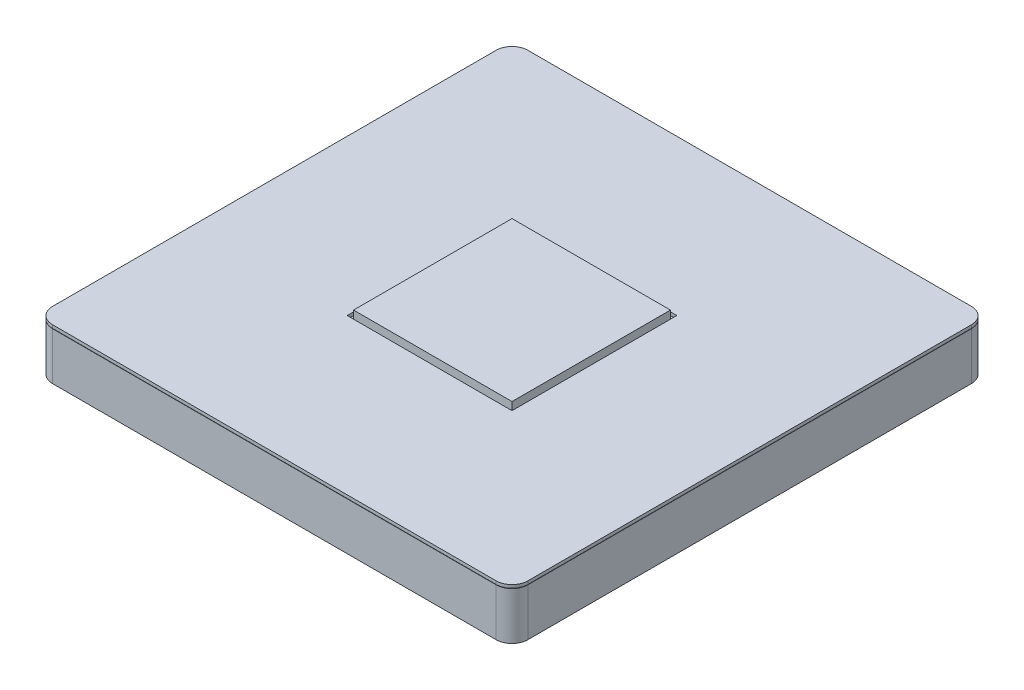
SolidWorks part; units mm, degrees
ref_plane "前视基准面" through (0, 0, 0) normal (0, 0, 1) x (1, 0, 0)
ref_plane "上视基准面" through (0, 0, 0) normal (0, 1, 0) x (1, 0, 0)
ref_plane "右视基准面" through (0, 0, 0) normal (1, 0, 0) x (0, 0, -1)
sketch "草图1" plane through (0, 0, 0) normal (0, 1, 0) x (1, 0, 0)
  line L1 (-7.5, -7.5) -> (7.5, -7.5)
  line L2 (-7.5, -7.5) -> (-7.5, 7.5)
  line L3 (-7.5, 7.5) -> (7.5, 7.5)
  line L4 (7.5, -7.5) -> (7.5, 7.5)
  line L5 (-7.5, -7.5) -> (7.5, 7.5) construction
  line L6 (-7.5, 7.5) -> (7.5, -7.5) construction
  point P0 (0, 0)
  dimension "D1" = 15
  dimension "D2" = 45
extrude "凸台-拉伸1" add sketch "草图1" along normal blind 1.5
fillet "圆角1" radius 0.5 4 edges at (-7.5, 0.75, 7.5) (-7.5, 0.75, -7.5) (7.5, 0.75, -7.5) (7.5, 0.75, 7.5)
ref_plane "基准面1" through (0, 1.51, 0) normal (0, 1, 0) x (1, 0, 0)
sketch "草图2" plane through (0, 1.51, 0) normal (0, 1, 0) x (1, 0, 0)
  line L1 (-2.6, -2.6) -> (2.6, -2.6)
  line L2 (-2.6, -2.6) -> (-2.6, 2.6)
  line L3 (-2.6, 2.6) -> (2.6, 2.6)
  line L4 (-7.5, 7) -> (-7.5, -7)
  line L5 (-7, -7.5) -> (7, -7.5)
  line L6 (7.5, -7) -> (7.5, 7)
  line L7 (7, 7.5) -> (-7, 7.5)
  line L8 (-7.5, 7) -> (-7.5, -7)
  line L9 (-7, -7.5) -> (7, -7.5)
  line L10 (7.5, -7) -> (7.5, 7)
  line L11 (7, 7.5) -> (-7, 7.5)
  line L12 (2.6, -2.6) -> (2.6, 2.6)
  line L13 (-2.6, -2.6) -> (2.6, 2.6) construction
  line L14 (-2.6, 2.6) -> (2.6, -2.6) construction
  arc A4 (-7.5, -7) -> (-7, -7.5) centre (-7, -7) ccw
  arc A5 (7, -7.5) -> (7.5, -7) centre (7, -7) ccw
  arc A6 (7.5, 7) -> (7, 7.5) centre (7, 7) ccw
  arc A7 (-7, 7.5) -> (-7.5, 7) centre (-7, 7) ccw
  arc A8 (-7.5, -7) -> (-7, -7.5) centre (-7, -7) ccw
  arc A9 (7, -7.5) -> (7.5, -7) centre (7, -7) ccw
  arc A10 (7.5, 7) -> (7, 7.5) centre (7, 7) ccw
  arc A11 (-7, 7.5) -> (-7.5, 7) centre (-7, 7) ccw
  point P2 (0, 0)
  dimension "D2" = 5.2
  dimension "D3" = 45
  dimension "D1" = 0
extrude "凸台-拉伸2" add sketch "草图2" along normal blind 0.1
sketch "草图3" plane through (0, 1.51, 0) normal (0, 1, 0) x (1, 0, 0)
  line L1 (-2.5, -2.5) -> (2.5, -2.5)
  line L2 (-2.5, -2.5) -> (-2.5, 2.5)
  line L3 (-2.5, 2.5) -> (2.5, 2.5)
  line L4 (2.5, -2.5) -> (2.5, 2.5)
  line L5 (-2.5, -2.5) -> (2.5, 2.5) construction
  line L6 (-2.5, 2.5) -> (2.5, -2.5) construction
  point P0 (0, 0)
  dimension "D1" = 5
  dimension "D2" = 45
extrude "凸台-拉伸3" add sketch "草图3" along normal blind 0.25 separate body
ref_plane "基准面2" through (0, 0, 0) normal (-1, 0, 0) x (0, 0, 1)
ref_plane "基准面3" through (0, 0, 0) normal (0, 0, -1) x (-1, 0, 0)
